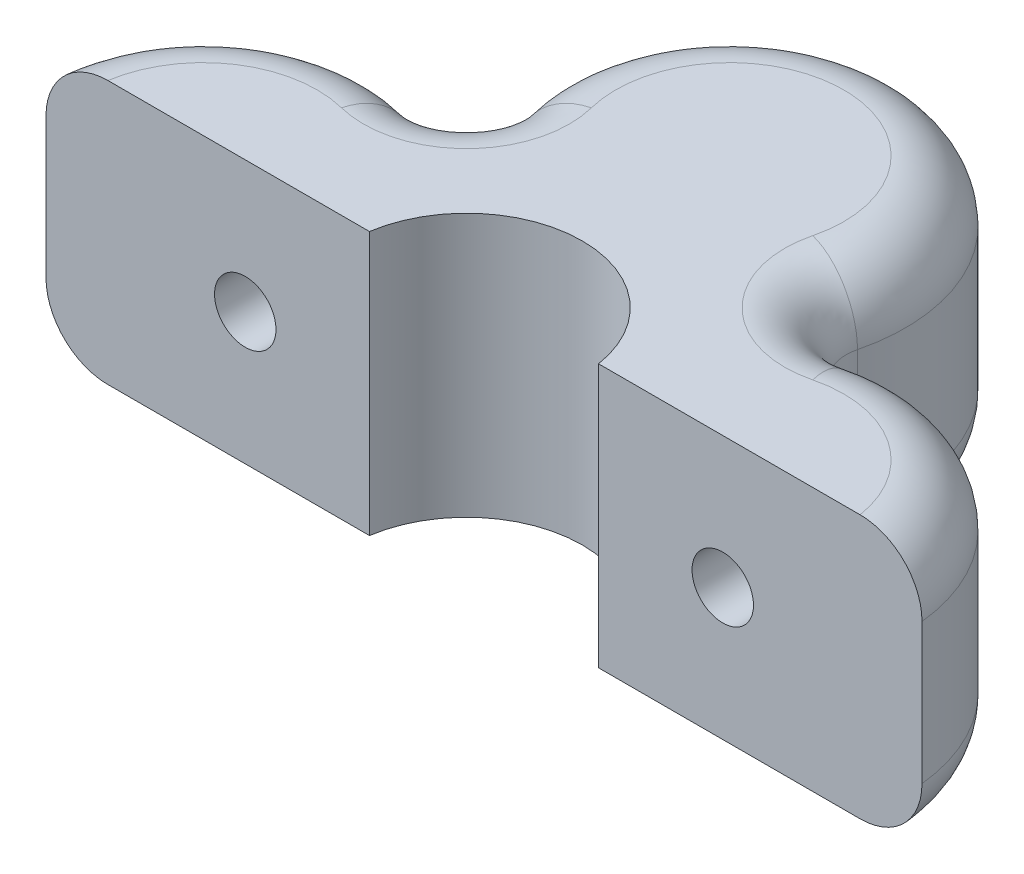
SolidWorks part; units mm, degrees
ref_plane "Front Plane" through (0, 0, 0) normal (0, 0, 1) x (1, 0, 0)
ref_plane "Top Plane" through (0, 0, 0) normal (0, 1, 0) x (1, 0, 0)
ref_plane "Right Plane" through (0, 0, 0) normal (1, 0, 0) x (0, 0, -1)
sketch "Sketch1" plane through (0, 0, 0) normal (0, 1, 0) x (1, 0, 0)
  line L0 (-6.6, 0) -> (-14.6, 0)
  line L3 (6.6, 0) -> (14.6, 0)
  arc A0 (-6.6, 0) -> (6.6, 0) centre (0, 0) cw
  arc A1 (-14.6, 0) -> (14.6, 0) centre (0, 0) cw
  dimension "D1" = 6.6
  dimension "D2" = 8
extrude "Boss-Extrude1" add sketch "Sketch1" along normal blind 15
sketch "Sketch6" plane through (0, 0, 0) normal (0, -1, 0) x (1, 0, 0)
  line L1 (-25, 0) -> (-8.6418, 0)
  line L2 (-6.6, 0) -> (-14.6, 0) construction
  line L4 (25, 0) -> (8.6418, 0)
  line L5 (6.6, 0) -> (14.6, 0) construction
  arc A0 (-9.701, -12.5729) -> (9.701, -12.5729) centre (0, -15) ccw
  arc A1 (-10.3238, -10.3238) -> (-9.701, -12.5729) centre (-11.9982, -11.9982) cw
  arc A2 (-14.6, 0) -> (14.6, 0) centre (0, 0) ccw construction
  arc A3 (10.3238, -10.3238) -> (9.701, -12.5729) centre (11.9982, -11.9982) ccw
  arc A4 (-25, 0) -> (-12.5729, -9.701) centre (-15, 0) ccw
  arc A5 (-12.5729, -9.701) -> (-10.3238, -10.3238) centre (-11.9982, -11.9982) cw
  arc A6 (25, 0) -> (12.5729, -9.701) centre (15, 0) cw
  arc A7 (12.5729, -9.701) -> (10.3238, -10.3238) centre (11.9982, -11.9982) ccw
  arc A8 (-8.6418, 0) -> (8.6418, 0) centre (0, 0) ccw
  point P10 (0, 0)
  point P16 (-12.5729, -9.701)
  point P25 (-11.9982, -11.9982)
  dimension "D1" = 10
  dimension "D7" = 10
  dimension "D2" = 15
  dimension "D4" = 10
  dimension "D5" = 15
  dimension "D8" = 15
extrude "Boss-Extrude2" add sketch "Sketch6" against normal up to surface (15 mm away) up to face at (0, 15, -5.3)
sketch "Sketch2" plane through (0, 0, 0) normal (0, 0, -1) x (-1, 0, 0)
  line L1 (-6.6, 15) -> (-6.6, 0) construction
  line L2 (6.6, 15) -> (6.6, 0) construction
  circle A0 centre (-13.6, 7.5) radius 1.75
  circle A1 centre (13.6, 7.5) radius 1.75
  dimension "D1" = 3.5
  dimension "D2" = 3.5
  dimension "D3" = 7.5
  dimension "D4" = 7
  dimension "D5" = 7
extrude "Cut-Extrude1" cut sketch "Sketch2" along normal up to next
sketch "Sketch5" plane through (0, 15, 0) normal (0, 1, 0) x (1, 0, 0)
  line L1 (-40.9608, 0) -> (37.8294, 0)
  line L2 (-40.9608, 0) -> (-40.9608, 1)
  line L3 (-40.9608, 1) -> (37.8294, 1)
  line L4 (37.8294, 0) -> (37.8294, 1)
  dimension "D1" = 1
extrude "Cut-Extrude4" cut sketch "Sketch5" against normal up to next
ref_plane "Plane1" through (0, 0, -15) normal (0, 0, 1) x (1, 0, 0)
sketch "Sketch3" plane through (0, 0, -15) normal (0, 0, 1) x (1, 0, 0)
  line L3 (-10.8, 5.8834) -> (-10.8, 9.1166)
  line L4 (-10.8, 9.1166) -> (-13.6, 10.7332)
  line L5 (-13.6, 10.7332) -> (-16.4, 9.1166)
  line L6 (-16.4, 9.1166) -> (-16.4, 5.8834)
  line L7 (-16.4, 5.8834) -> (-13.6, 4.2668)
  line L8 (-13.6, 4.2668) -> (-10.8, 5.8834)
  circle A1 centre (13.6, 7.5) radius 3.25
  circle A2 centre (-13.6, 7.5) radius 2.8 construction
  dimension "D1" = 6.5
  dimension "D2" = 5.6
extrude "Cut-Extrude2" cut sketch "Sketch3" along normal offset from surface (9 mm away) 5 up to face at (-15.7368, 7.5, -1)
fillet "Fillet1" radius 3.5 10 edges at (20.7511, 15, -8.1808) (20.7511, 0, -8.1808) (10.3238, 0, -10.3238) (10.3238, 15, -10.3238) (0, 15, -25) (0, 0, -25) (-10.3238, 15, -10.3238) (-10.3238, 0, -10.3238) (-20.7511, 0, -8.1808) (-20.7511, 15, -8.1808)
